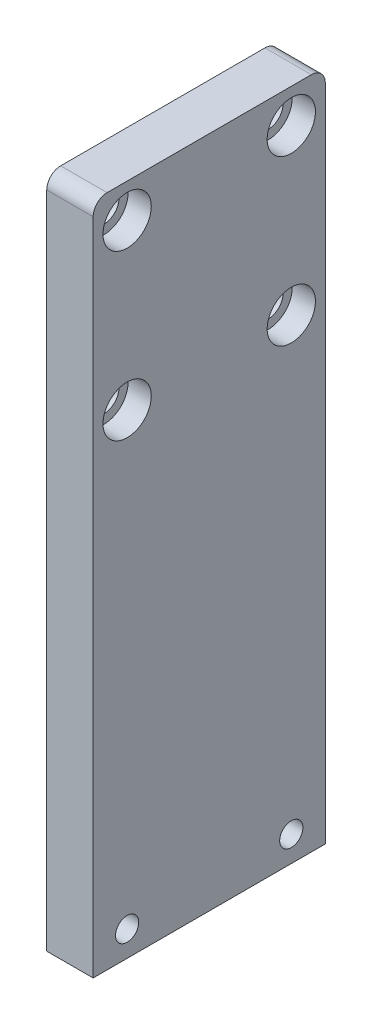
SolidWorks part; units mm, degrees
ref_plane "Alzado" through (0, 0, 0) normal (0, 0, 1) x (1, 0, 0)
ref_plane "Planta" through (0, 0, 0) normal (0, 1, 0) x (1, 0, 0)
ref_plane "Vista lateral" through (0, 0, 0) normal (1, 0, 0) x (0, 0, -1)
sketch "Croquis1" plane through (0, 0, 0) normal (1, 0, 0) x (0, 0, -1)
  line L1 (-25, -120) -> (25, -120)
  line L2 (25, -120) -> (25, 25)
  line L4 (0, 25) -> (0, -120) construction
  line L5 (25, 0) -> (-25, 0) construction
  line L6 (-25, 0) -> (-25, 25)
  line L7 (-25, 0) -> (-25, -120)
  line L8 (-25, 25) -> (0, 25)
  line L9 (0, 25) -> (25, 25)
  line L10 (0, 5.5) -> (0, -5.5) construction
  circle A1 centre (-17.68, 17.68) radius 3.25
  circle A2 centre (17.68, 17.68) radius 3.25
  circle A3 centre (17.68, -17.68) radius 3.25
  circle A4 centre (-17.68, -17.68) radius 3.25
  circle A5 centre (-17.68, -114.5) radius 2.5
  circle A6 centre (17.68, -114.5) radius 2.5
  dimension "D7" = 6.5
  dimension "D11" = 6.5
  dimension "D13" = 5
  dimension "D1" = 25
  dimension "D2" = 25
  dimension "D3" = 17.68
  dimension "D4" = 17.68
  dimension "D5" = 17.68
  dimension "D6" = 120
  dimension "D8" = 17.68
  dimension "D9" = 0
  dimension "D10" = 25
  dimension "D14" = 5.5
  dimension "D15" = 7.32
extrude "Saliente-Extruir1" add sketch "Croquis1" along normal blind 10
sketch "Croquis5" plane through (10, 0, 0) normal (1, 0, 0) x (0, 0, -1)
  circle A0 centre (17.68, 17.68) radius 5.2
  circle A1 centre (-17.68, 17.68) radius 5.2
  circle A2 centre (-17.68, -17.68) radius 5.2
  circle A3 centre (17.68, -17.68) radius 5.2
  dimension "D1" = 10.4
  dimension "D2" = 10.4
  dimension "D3" = 10.4
  dimension "D4" = 10.4
extrude "Cortar-Extruir2" cut sketch "Croquis5" against normal blind 5
fillet "Fillet1" radius 3 2 edges at (5, 25, -25) (5, 25, 25)
